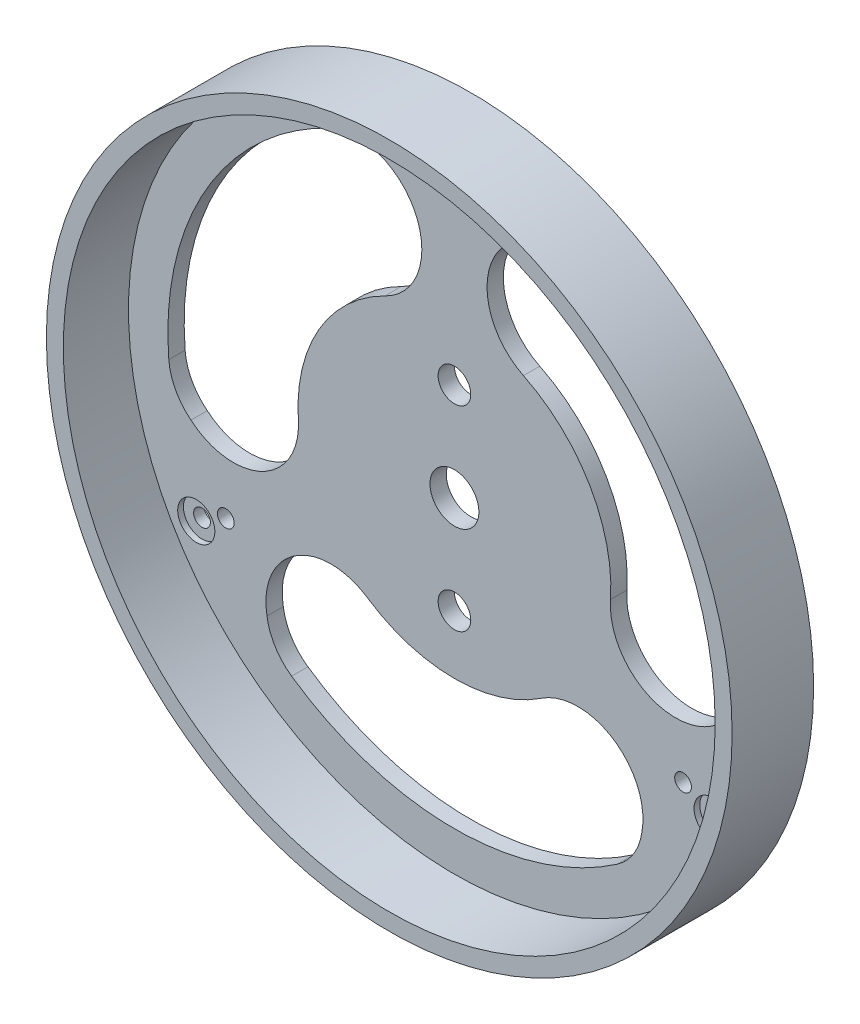
SolidWorks part; units mm, degrees
ref_plane "Front Plane" through (0, 0, 0) normal (0, 0, 1) x (1, 0, 0)
ref_plane "Top Plane" through (0, 0, 0) normal (0, 1, 0) x (1, 0, 0)
ref_plane "Right Plane" through (0, 0, 0) normal (1, 0, 0) x (0, 0, -1)
sketch "Sketch1" plane through (0, 0, 0) normal (0, 0, 1) x (1, 0, 0)
  circle A0 centre (0, 0) radius 63.5
  circle A1 centre (0, 0) radius 66.8
  dimension "D1" = 127
  dimension "D2" = 133.6
extrude "Boss-Extrude1" add sketch "Sketch1" along normal blind 15.88
sketch "Sketch2" plane through (0, 0, 0) normal (0, 0, 1) x (1, 0, 0)
  circle A0 centre (0, 0) radius 63.5
extrude "Boss-Extrude2" add sketch "Sketch2" along normal blind 3.18
sketch "Sketch6" plane through (0, 0, 3.18) normal (0, 0, 1) x (1, 0, 0)
  arc A0 (-23.9274, 50.4422) -> (-55.6481, -4.4961) centre (0, 0) ccw
  arc A1 (-13.5362, 27.3094) -> (-30.4121, -2.0331) centre (0, 0) ccw
  arc A3 (-13.5362, 27.3094) -> (-14.8174, 50.724) centre (-19.05, 38.75) ccw
  arc A6 (-14.8174, 50.724) -> (-23.9274, 50.4422) centre (-19.05, 40.16) ccw
  arc A8 (-51.3277, -12.5323) -> (-30.4121, -2.0331) centre (-43.08, -2.88) ccw
  arc A9 (-55.6481, -4.4961) -> (-51.3277, -12.5323) centre (-44.31, -3.58) ccw
  dimension "D1" = 111.659
  dimension "D2" = 60.96
  dimension "D14" = 25.4
  dimension "D3" = 44.31
  dimension "D4" = 3.58
  dimension "D6" = 2.88
  dimension "D7" = 43.08
  dimension "D9" = 40.16
  dimension "D10" = 19.05
  dimension "D12" = 38.75
  dimension "D13" = 19.05
extrude "Cut-Extrude2" cut sketch "Sketch6" against normal through all
sketch "Sketch5" plane through (0, 0, 3.18) normal (0, 0, 1) x (1, 0, 0)
  line L0 (0, -8.734) -> (0, 8.734) construction
  circle A0 centre (0, 0) radius 4.7625
  circle A1 centre (0, 19.05) radius 3.18
  dimension "D1" = 9.525
  dimension "D5" = 19.05
  dimension "D2" = 6.36
extrude "Cut-Extrude1" cut sketch "Sketch5" against normal through all
sketch "Sketch7" plane through (0, 0, 3.18) normal (0, 0, 1) x (1, 0, 0)
  line L0 (0, 0) -> (0, 17.6305) construction
pattern_circular "CirPattern2" count 3 over 360 about axis through (0, 0, 0) along (0, 0, 1) of "Cut-Extrude2"
pattern_circular "CirPattern3" count 2 over 360 about axis through (0, 0, 0) along (0, 0, 1) of "Cut-Extrude1"
hole_wizard "Hole1" positions "Sketch14" profile "Sketch16" hole size "#4" standard "ANSI Inch" end condition through all
sketch "Sketch14" plane through (0, 0, 0) normal (0, 0, -1) x (-1, 0, 0)
  line L0 (0, 8.734) -> (0, -8.734) construction
  point P0 (0, 58.0746)
  dimension "D1" = 58.0746
sketch "Sketch16" plane through (0, 58.0746, 0) normal (1, 0, 0) x (0, 1, 0)
  line L0 (0, 0) -> (0, 15.88)
  line L1 (0, 15.88) -> (1.6319, 15.88)
  line L2 (1.6319, 15.88) -> (1.6319, 0)
  line L5 (1.6319, 0) -> (0, 0)
  line L11 (0, -6.35) -> (0, 107.95) construction
  dimension "Thru Hole Dia." = 3.2639
  dimension "Thru Hole Depth" = 15.88
pattern_circular "CirPattern5" count 3 over 240 about axis through (0, 0, 0) along (0, 0, 1) of "Hole1"
hole_wizard "Hole2" positions "Sketch17" profile "Sketch19" hole size "#4" standard "ANSI Inch" end condition through all
sketch "Sketch17" plane through (0, 0, 0) normal (0, 0, -1) x (-1, 0, 0)
  line L0 (0, 8.734) -> (0, -8.734) construction
  point P0 (0, 51.435)
  dimension "D1" = 51.435
sketch "Sketch19" plane through (0, 51.435, 0) normal (1, 0, 0) x (0, 1, 0)
  line L0 (0, 0) -> (0, 15.88)
  line L1 (0, 15.88) -> (1.6319, 15.88)
  line L2 (1.6319, 15.88) -> (1.6319, 0)
  line L5 (1.6319, 0) -> (0, 0)
  line L11 (0, -6.35) -> (0, 107.95) construction
  dimension "Thru Hole Dia." = 3.2639
  dimension "Thru Hole Depth" = 15.88
pattern_circular "CirPattern6" count 3 every 120 about axis through (0, 0, 0) along (0, 0, 1) of "Hole2"
hole_wizard "Ø1.0 (1) Diameter Hole1" positions "3DSketch1" profile "Sketch20" hole size "Ø1.0" standard "AS"
sketch3d "3DSketch1"
  line L0 (0, 58.0746, 3.18) -> (0, 58.0746, 0) construction
  point P0 (0, 58.0746, 3.18)
sketch "Sketch20" plane through (0, 58.0746, 3.18) normal (1, 0, 0) x (0, -1, 0)
  line L0 (0, 0) -> (0, 1.1176)
  line L1 (0, 1.1176) -> (3.6195, 1.1176)
  line L2 (3.6195, 1.1176) -> (3.6195, 0)
  line L5 (3.6195, 0) -> (0, 0)
  line L10 (0, 1.1176) -> (-3.6195, 1.1176) construction
  line L11 (0, -6.35) -> (0, 107.95) construction
  dimension "Hole Dia." = 7.239
  dimension "Hole Depth" = 1.1176
  dimension "Drill Angle" = 180
pattern_circular "CirPattern7" count 3 every 120 about axis through (0, 0, 0) along (0, 0, 1) of "Ø1.0 (1) Diameter Hole1"
